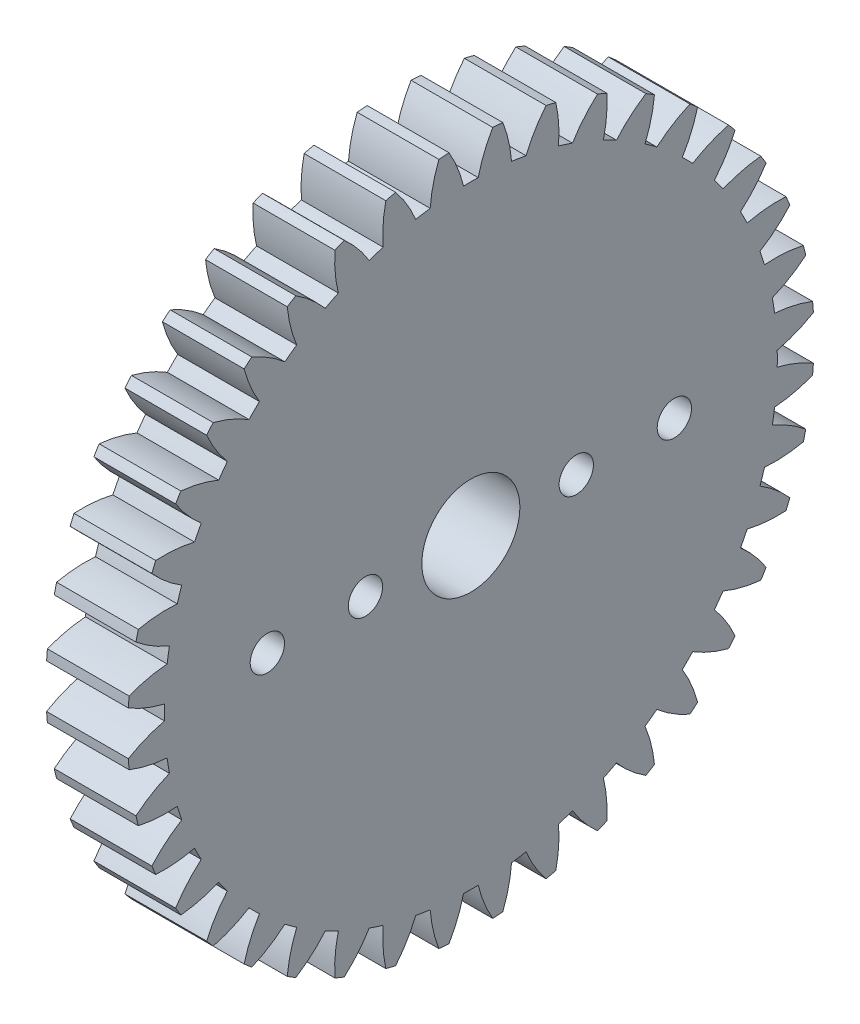
SolidWorks part; units mm, degrees
ref_plane "Plane1" through (0, 0, 0) normal (0, 0, 1) x (1, 0, 0)
ref_plane "Plane2" through (0, 0, 0) normal (0, 1, 0) x (1, 0, 0)
ref_plane "Plane3" through (0, 0, 0) normal (1, 0, 0) x (0, 0, -1)
sketch "HoldingSke" plane through (0, 0, 0) normal (0, 1, 0) x (1, 0, 0)
  line L0 (0, 0) -> (0.766, -0.6428)
  line L1 (-15, 0) -> (100, 0) construction
  line L2 (0, 0) -> (-2.1039, 2.3779)
  line L3 (0, 0) -> (-11.863, 4.5341)
  line L4 (0, 0) -> (6.6156, 5.5511)
  line L5 (0, 0) -> (-46.8476, -17.4728)
  line L6 (0, 0) -> (-4.1448, -2.7965)
  line L7 (-2.1039, 2.3779) -> (8.6586, 51.2059)
  line L8 (-76.2, 54.61) -> (-76.1, 54.61)
  line L9 (-71.009, 38.7566) -> (-53.1078, 45.2721)
  line L10 (-76.2, 71.12) -> (104.1128, 71.12)
  line L11 (0, 0) -> (-5, 0)
  line L12 (-76.2, 101.6) -> (-76.162, 101.6)
  line L13 (24.9733, 27.94) -> (52.9518, 28.4284)
  line L14 (24.9733, 27.94) -> (24.9743, 27.94)
  line L15 (24.9733, 27.94) -> (100.4006, 29.5858)
  line L16 (-63.627, -1) -> (-12.827, -1)
  circle A0 centre (0, 0) radius 0.5
  circle A1 centre (0, 0) radius 18.749
  circle A2 centre (0, 0) radius 37.5
  circle A3 centre (0, 0) radius 0.5
  dimension "MHD" = 37.498
  dimension "Hub_dia" = 75
  dimension "Bore" = 1
  dimension "MBD" = 1
  dimension "Num_teeth" = 40
  dimension "Pitch" = 1
  dimension "Overall_len" = 50
  dimension "Show_teeth" = 40
  dimension "Thickness" = 5
  dimension "OAL" = 50.0001
  dimension "T_dim" = 0.1
  dimension "Ap" = 20
  dimension "H" = 19.05
  dimension "Pitch_radius" = 180.3128
  dimension "Width" = 5
  dimension "Backlash" = 0.038
  dimension "Addendum_fac" = 1
  dimension "Dedendum_fac" = 1.25
  dimension "Clearance_fac" = 0.25
  dimension "Dedendum_add" = 0.001
  dimension "Module" = 1
sketch "BasProSke" plane through (0, 0, 0) normal (0, 1, 0) x (1, 0, 0)
  line L0 (-10, 0) -> (60, 0) construction
  line L1 (0, 0) -> (0, 21)
  line L2 (0, 0) -> (5, 0)
  line L3 (5, 0) -> (5, 21)
  line L4 (5, 21) -> (0, 21)
  dimension "Thickness" = 5
  dimension "Diameter" = 42
revolve "Base-Revolve" add sketch "BasProSke" angle 360 about L0
sketch "TooCutSke" plane through (0, 0, 0) normal (1, 0, 0) x (0, 0, -1)
  line L1 (0, 0) -> (0, 107) construction
  line L2 (0, 0) -> (-0.8517, 19.9819) construction
  line L3 (0, 0) -> (-3.1363, 39.8509) construction
  line L4 (-0.8517, 19.9819) -> (-1.5682, 19.9255) construction
  arc A0 (0.4487, 18.7436) -> (-0.4487, 18.7436) centre (0, 0) ccw
  arc A1 (1.3547, 20.9817) -> (-1.3547, 20.9817) centre (0, 0) ccw
  circle A2 centre (0, 0) radius 20 construction
  circle A3 centre (0, 0) radius 18.7939 construction
  arc A4 (-0.4487, 18.7436) -> (-1.3547, 20.9817) centre (-8.2322, 16.895) ccw
  arc A5 (1.3547, 20.9817) -> (0.4487, 18.7436) centre (8.2322, 16.895) ccw
  dimension "Root_dia" = 37.498
  dimension "Overcut_dia" = 42.0508
  dimension "Pitch_dia" = 40
  dimension "Base_dia" = 37.5877
  dimension "Flank_rad" = 8
  dimension "Half_ang" = 4.5
  dimension "Half_CT" = 0.7187
extrude "ToothCut" cut sketch "TooCutSke" along normal through all
fillet "Breaks" [suppressed] radius 0.02
fillet "RootFillets" [suppressed] radius 0.251
pattern_circular "TeethCuts" count 40 every 9 about axis through (-10, 0, 0) along (1, 0, 0) of "ToothCut", "RootFillets", "Breaks"
sketch "HubNeaOneSke" plane through (0, 0, 0) normal (-1, 0, 0) x (0, 0, 1)
  circle A0 centre (0, 0) radius 18.749
  dimension "Diameter" = 37.498
extrude "HubNearOne" [suppressed] add sketch "HubNeaOneSke" along normal blind 45.0001
sketch "HubNeaBotSke" plane through (0, 0, 0) normal (-1, 0, 0) x (0, 0, 1)
  circle A0 centre (0, 0) radius 18.749
  dimension "Diameter" = 37.498
extrude "HubNearBoth" [suppressed] add sketch "HubNeaBotSke" along normal blind 22.5001
ref_plane "FarPln" through (5, 0, 0) normal (1, 0, 0) x (0, 0, -1)
sketch "HubFarSke" plane through (5, 0, 0) normal (1, 0, 0) x (0, 0, -1)
  circle A0 centre (0, 0) radius 18.749
  dimension "Diameter" = 37.498
extrude "HubFar" [suppressed] add sketch "HubFarSke" along normal blind 22.5001
sketch "BorSke" plane through (0, 0, 0) normal (1, 0, 0) x (0, 0, -1)
  circle A0 centre (0, 0) radius 0.5
  dimension "Diameter" = 1
extrude "Bore" cut sketch "BorSke" along normal mid plane 100.0002
sketch "KeySke" plane through (0, 0, 0) normal (1, 0, 0) x (0, 0, -1)
  line L0 (-0.05, 0) -> (-0.05, 0.6)
  line L1 (-0.05, 0.6) -> (0.05, 0.6)
  line L2 (0.05, 0.6) -> (0.05, 0)
  line L3 (0, 0) -> (0, 34) construction
  line L4 (-0.05, 0) -> (0.05, 0)
  dimension "Offset" = 0.6
  dimension "Width" = 0.1
extrude "Keyway" [suppressed] cut sketch "KeySke" along normal mid plane 100.0002
pattern_circular "Keyway2" [suppressed] count 2 every 90 about axis through (-10, 0, 0) along (1, 0, 0)
sketch "ｽｹｯﾁ1" plane through (5, 0, 0) normal (1, 0, 0) x (0, 0, -1)
  line L0 (0, 0) -> (0, 9.8146) construction
  circle A0 centre (-12.45, 0) radius 1.05
  circle A1 centre (-6.45, 0) radius 1.05
  circle A2 centre (0, 0) radius 3
  circle A3 centre (6.45, 0) radius 1.05
  circle A4 centre (12.45, 0) radius 1.05
  point P2 (0, 0)
  dimension "D1" = 2.1
  dimension "D3" = 6
  dimension "D4" = 6
  dimension "D2" = 12.45
extrude "ｶｯﾄ - 押し出し1" cut sketch "ｽｹｯﾁ1" against normal through all
equation "' \"Module@HoldingSke\" = 6.35"
equation "' \"Num_teeth@HoldingSke\" = 12"
equation "' \"Ap@HoldingSke\" =  20"
equation "' \"Ap@HoldingSke\" = 20"
equation "' \"Width@HoldingSke\" = 0.5 * 25.4"
equation "' \"Hub_dia@HoldingSke\"= 1 * 25.4"
equation "' \"Hub_dia@HoldingSke\" = 1 * 25.4"
equation "' \"Overall_len@HoldingSke\" = 1.0 * 25.4"
equation "' \"Bore@HoldingSke\" = 0.75 * 25.4"
equation "' \"T_dim@HoldingSke\" = 0.1 * 25.4"
equation "' \"Width@KeySke\" = 0.25 * 25.4"
equation "' \"Show_teeth@HoldingSke\" = 13"
equation "' \"Backlash@HoldingSke\" = 0.009 * 25.4"
equation "' \"Addendum_fac@HoldingSke\" = 1.0"
equation "' \"Dedendum_fac@HoldingSke\" = 1.25"
equation "' \"Dedendum_add@HoldingSke\" = 0.00005 * 25.4"
equation "' \"Clearance_fac@HoldingSke\" = 0.25"
equation "\"Pitch@HoldingSke\" = 1 / \"Module@HoldingSke\""
equation "\"Overcut_dia@TooCutSke\" = (\"Num_teeth@HoldingSke\" + 2 * \"Addendum_fac@HoldingSke\") / \"Pitch@HoldingSke\" + 0.002 * 25.4"
equation "\"Pitch_dia@TooCutSke\" = \"Num_teeth@HoldingSke\" / \"Pitch@HoldingSke\""
equation "\"Base_dia@TooCutSke\" = \"Num_teeth@HoldingSke\" / \"Pitch@HoldingSke\" * cos((\"Ap@HoldingSke\"  * 3.14159265 / 180))"
equation "\"Root_dia@TooCutSke\" = (\"Num_teeth@HoldingSke\" + 2) / \"Pitch@HoldingSke\" - 2 * (\"Addendum_fac@HoldingSke\" + \"Dedendum_fac@HoldingSke\") / \"Pitch@HoldingSke\" - \"Dedendum_add@HoldingSke\" * 2"
equation "\"Half_ang@TooCutSke\" = 180 / \"Num_teeth@HoldingSke\""
equation "\"Half_CT@TooCutSke\" = \"Num_teeth@HoldingSke\" / \"Pitch@HoldingSke\" * sin((3.14159265 / 2 / \"Num_teeth@HoldingSke\")) / 2 - 7 * \"Backlash@HoldingSke\" / 4"
equation "\"Flank_rad@TooCutSke\" = \"Num_teeth@HoldingSke\" / \"Pitch@HoldingSke\" / 5"
equation "\"Radius@RootFillets\" = \"Clearance_fac@HoldingSke\" / \"Pitch@HoldingSke\" + \"Dedendum_add@HoldingSke\""
equation "\"Break_rad@Breaks\" = 0.02 / \"Pitch@HoldingSke\""
equation "\"Thickness@HoldingSke\" = \"Width@HoldingSke\""
equation "\"OAL@HoldingSke\" = \"Thickness@HoldingSke\""
equation "\"MHD@HoldingSke\" = (\"Num_teeth@HoldingSke\" + 2) / \"Pitch@HoldingSke\" - 2 * (\"Addendum_fac@HoldingSke\" + \"Dedendum_fac@HoldingSke\")  / \"Pitch@HoldingSke\" - \"Dedendum_add@HoldingSke\" * 2"
equation "\"MBD@HoldingSke\" = (\"Num_teeth@HoldingSke\" + 2) / \"Pitch@HoldingSke\" - 2 * (\"Addendum_fac@HoldingSke\" + \"Dedendum_fac@HoldingSke\")  / \"Pitch@HoldingSke\" - \"Dedendum_add@HoldingSke\" * 2 - 0.002 * 25.4"
equation "\"MHD@HoldingSke\" = ((sgn( \"MHD@HoldingSke\" - \"Hub_dia@HoldingSke\" )-1)*( \"MHD@HoldingSke\" - \"Hub_dia@HoldingSke\" ))/-2+ \"Hub_dia@HoldingSke\""
equation "\"MBD@HoldingSke\" = ((sgn( \"MBD@HoldingSke\" - \"Bore@HoldingSke\" )-1)*( \"MBD@HoldingSke\" - \"Bore@HoldingSke\" ))/-2+ \"Bore@HoldingSke\""
equation "\"OAL@HoldingSke\" = ((sgn( \"OAL@HoldingSke\" - \"Overall_len@HoldingSke\" )+1)*( \"OAL@HoldingSke\" - \"Overall_len@HoldingSke\" ))/2 + \"Overall_len@HoldingSke\" + 0.000002 * 25.4"
equation "\"Num_teeth@TeethCuts\" = int( \"Show_teeth@HoldingSke\" ) + 1"
equation "\"Num_teeth@TeethCuts\" = ((sgn( \"Num_teeth@TeethCuts\" - \"Num_teeth@HoldingSke\" )-1)*( \"Num_teeth@TeethCuts\" - \"Num_teeth@HoldingSke\" ))/-2+ \"Num_teeth@HoldingSke\""
equation "\"Num_teeth@TeethCuts\" = ((sgn( \"Num_teeth@TeethCuts\" - 2.0)+1)*( \"Num_teeth@TeethCuts\" - 2.0))/2 +2.0"
equation "\"Angle@TeethCuts\" = 360.0 / \"Num_teeth@HoldingSke\""
equation "\"Diameter@BasProSke\" = (\"Num_teeth@HoldingSke\" + 2 * \"Addendum_fac@HoldingSke\") / \"Pitch@HoldingSke\""
equation "\"Thickness@BasProSke\"  = \"Thickness@HoldingSke\""
equation "' \"Fillet_rad@BasProSke\" =  \"Thickness@HoldingSke\" * 0.05"
equation "' \"Fillet_rad@BasProSke\" = \"Thickness@HoldingSke\" * 0.05"
equation "\"MHD@HoldingSke\" = ((sgn( \"MHD@HoldingSke\" - \"Root_dia@TooCutSke\" )-1)*( \"MHD@HoldingSke\" - \"Root_dia@TooCutSke\" ))/-2+ \"Root_dia@TooCutSke\""
equation "\"Diameter@HubNeaOneSke\" = \"MHD@HoldingSke\""
equation "\"Length@HubNearOne\" = \"OAL@HoldingSke\" - \"Thickness@BasProSke\""
equation "\"Diameter@HubNeaBotSke\" = \"MHD@HoldingSke\""
equation "\"Length@HubNearBoth\" = ( \"OAL@HoldingSke\" - \"Thickness@BasProSke\" ) / 2.0"
equation "\"Thickness@FarPln\" = \"Thickness@BasProSke\""
equation "\"Diameter@HubFarSke\" = \"MHD@HoldingSke\""
equation "\"Length@HubFar\" = ( \"OAL@HoldingSke\" - \"Thickness@BasProSke\" ) / 2.0"
equation "\"Diameter@BorSke\" = \"MBD@HoldingSke\""
equation "\"D1@Bore\" = \"OAL@HoldingSke\" * 2.0"
equation "\"D1@Keyway\" = \"OAL@HoldingSke\" * 2.0"
equation "\"Offset@KeySke\" = \"T_dim@HoldingSke\" + \"MBD@HoldingSke\" / 2.0"
